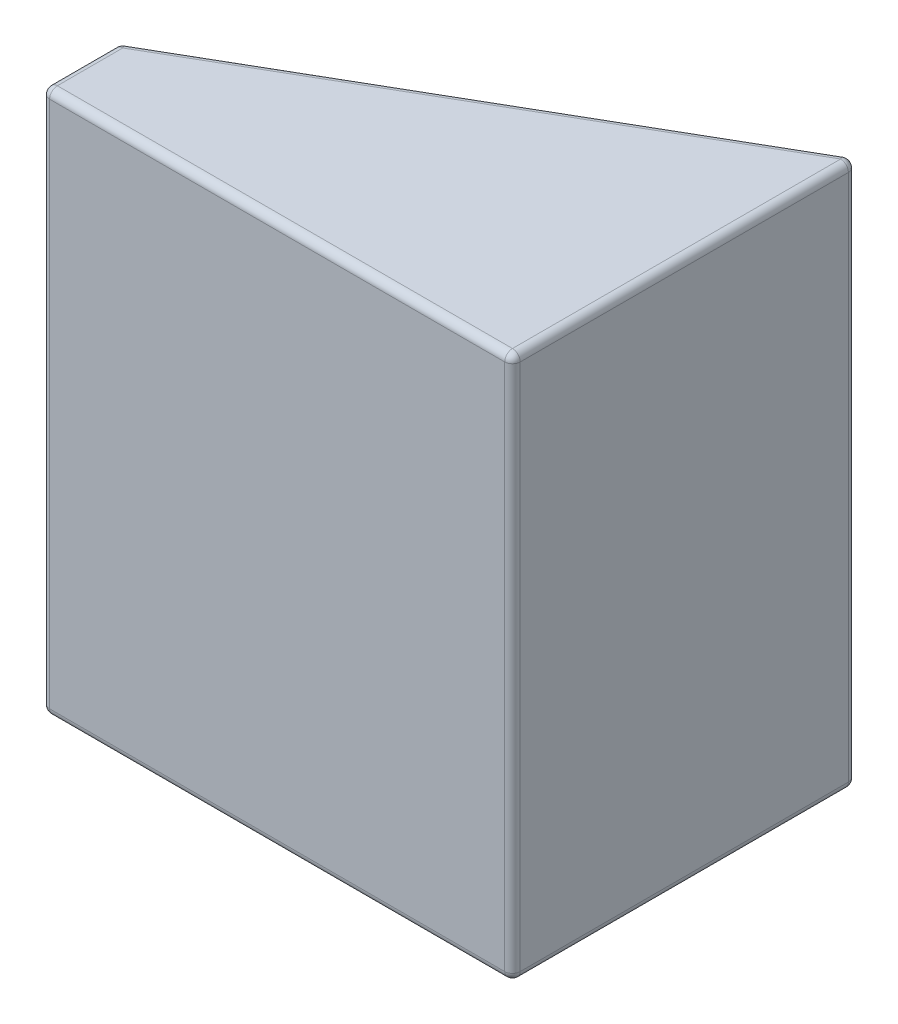
SolidWorks part; units mm, degrees
ref_plane "Front Plane" through (0, 0, 0) normal (0, 0, 1) x (1, 0, 0)
ref_plane "Top Plane" through (0, 0, 0) normal (0, 1, 0) x (1, 0, 0)
ref_plane "Right Plane" through (0, 0, 0) normal (1, 0, 0) x (0, 0, -1)
sketch "Sketch2" plane through (0, 0, 0) normal (0, 1, 0) x (1, 0, 0)
  line L0 (0, 0) -> (153.9793, 0)
  line L1 (0, 0) -> (153.9793, 88.9)
  line L2 (153.9793, 88.9) -> (153.9793, 0)
  dimension "D1" = 177.8
  dimension "D2" = 88.9
extrude "Boss-Extrude1" add sketch "Sketch2" along normal blind 177.8 contours L1 L2 L0
sketch "Sketch3" plane through (0, 0, 0) normal (-0.5, 0, -0.866) x (-0.866, 0, 0.5)
  line L0 (-88.9, 177.8) -> (-88.9, 88.9) construction
  line L2 (-177.8, 88.9) -> (-88.9, 88.9) construction
  line L3 (-177.8, 177.8) -> (-177.8, 0) construction
  line L4 (0, 177.8) -> (-177.8, 177.8) construction
  circle A0 centre (-88.9, 88.9) radius 73.2155
  dimension "D2" = 146.431
  dimension "D1" = 88.9
ref_plane "Plane1" through (0, 0, 0) normal (0, -1, 0) x (-1, 0, 0)
sketch "Sketch4" plane through (0, 0, 0) normal (0, -1, 0) x (-1, 0, 0)
  line L1 (-153.9793, 0) -> (0, 0)
  line L2 (-153.9793, 0) -> (-153.9793, -25.4)
  line L3 (-153.9793, -25.4) -> (0, -25.4)
  line L4 (0, 0) -> (0, -25.4)
  dimension "D1" = 25.4
extrude "Boss-Extrude4" add sketch "Sketch4" against normal up to surface (177.8 mm away) up to face at (102.6529, 177.8, -29.6333)
extrude "Cut-Extrude2" cut sketch "Sketch3" against normal blind 25.4 contours A0
fillet "Fillet1" radius 2.54 13 edges at (76.9897, 177.8, 25.4) (76.9897, 0, 25.4) (153.9793, 88.9, 25.4) (153.9793, 177.8, -31.75) (153.9793, 0, -31.75) (0, 177.8, 12.7) (0, 0, 12.7) (0, 88.9, 25.4) (0, 88.9, 0) (76.9897, 0, -44.45) (76.9897, 177.8, -44.45) (153.9793, 88.9, -88.9) (13.5832, 88.9, -7.8423)
